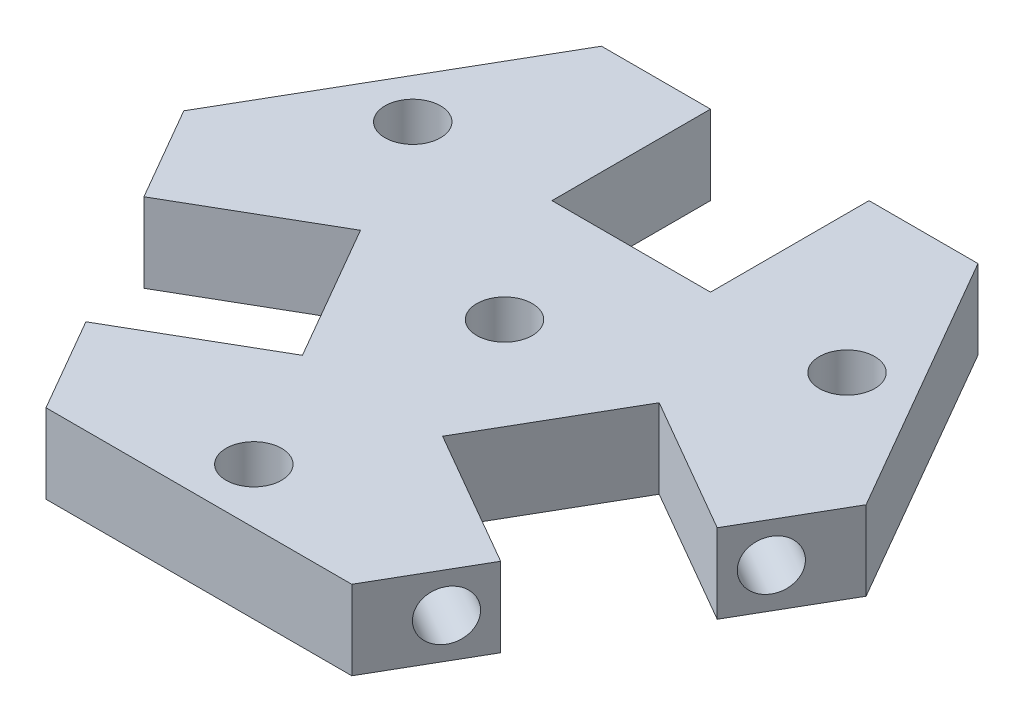
SolidWorks part; units mm, degrees
ref_plane "Front Plane" through (0, 0, 0) normal (0, 0, 1) x (1, 0, 0)
ref_plane "Top Plane" through (0, 0, 0) normal (0, 1, 0) x (1, 0, 0)
ref_plane "Right Plane" through (0, 0, 0) normal (1, 0, 0) x (0, 0, -1)
sketch "Sketch1" plane through (0, 0, 0) normal (0, 1, 0) x (1, 0, 0)
  line L1 (0, 16.5) -> (-14.2894, -8.25)
  line L2 (-14.2894, -8.25) -> (14.2894, -8.25)
  line L3 (14.2894, -8.25) -> (0, 16.5)
  line L4 (-10, 10.15) -> (10, 10.15)
  line L5 (-10, 10.15) -> (-10, 22.85)
  line L6 (-10, 22.85) -> (10, 22.85)
  line L7 (10, 10.15) -> (10, 22.85)
  line L8 (-10, 10.15) -> (10, 22.85) construction
  line L9 (-10, 22.85) -> (10, 10.15) construction
  line L17 (-14.7887, -20.0853) -> (-24.7887, -2.7647)
  line L18 (-13.7902, 3.5853) -> (-24.7887, -2.7647)
  line L19 (-11.9652, 0.4243) -> (-22.9637, -5.9257)
  line L20 (-3.7902, -13.7353) -> (-13.7902, 3.5853)
  line L21 (-6.35, 10.15) -> (6.35, 10.15)
  line L22 (-6.35, 10.15) -> (-6.35, 22.85)
  line L23 (-6.35, 22.85) -> (6.35, 22.85)
  line L24 (6.35, 10.15) -> (6.35, 22.85)
  line L25 (-6.35, 10.15) -> (6.35, 22.85) construction
  line L26 (-6.35, 22.85) -> (6.35, 10.15) construction
  line L27 (-5.6152, -10.5743) -> (-16.6137, -16.9243)
  line L28 (-3.7902, -13.7353) -> (-14.7887, -20.0853)
  line L29 (24.7887, -2.7647) -> (14.7887, -20.0853)
  line L30 (3.7902, -13.7353) -> (14.7887, -20.0853)
  line L31 (5.6152, -10.5743) -> (16.6137, -16.9243)
  line L32 (13.7902, 3.5853) -> (3.7902, -13.7353)
  line L33 (11.9652, 0.4243) -> (22.9637, -5.9257)
  line L34 (13.7902, 3.5853) -> (24.7887, -2.7647)
  line L35 (-10, 22.85) -> (14.7887, -20.0853)
  line L36 (10, 22.85) -> (-14.7887, -20.0853)
  line L37 (24.7887, -2.7647) -> (-24.7887, -2.7647)
  line L38 (-10, 22.85) -> (-24.7887, -2.7647)
  line L39 (10, 22.85) -> (24.7887, -2.7647)
  line L40 (14.7887, -20.0853) -> (-14.7887, -20.0853)
  line L41 (-24.7887, -2.7647) -> (-14.7887, -20.0853)
  line L42 (-14.7887, -20.0853) -> (-12.2487, -24.4847)
  line L43 (24.7887, -2.7647) -> (12.2487, -24.4847)
  line L44 (12.2487, -24.4847) -> (-12.2487, -24.4847)
  line L45 (-27.3287, 1.6347) -> (-15.08, 22.85)
  line L46 (-10, 22.85) -> (-15.08, 22.85)
  line L47 (-14.7887, -20.0853) -> (-27.3287, 1.6347)
  line L48 (15.08, 22.85) -> (27.3287, 1.6347)
  line L49 (24.7887, -2.7647) -> (27.3287, 1.6347)
  line L50 (-10, 22.85) -> (15.08, 22.85)
  circle A0 centre (0, 0) radius 8.25 construction
  circle A1 centre (0, 0) radius 2.2225
  circle A2 centre (0, -20.0853) radius 2.2225
  circle A3 centre (17.3943, 10.0426) radius 2.2225
  circle A4 centre (-17.3943, 10.0426) radius 2.2225
  dimension "D1" = 16.5
  dimension "D7" = 5.08
  dimension "D2" = 12.7
  dimension "D3" = 20
  dimension "D5" = 12.7
  dimension "D6" = 12.7
  dimension "D4" = 3
  dimension "D8" = 3
extrude "Boss-Extrude3" add sketch "Sketch1" along normal blind 6.35 contours L5 L38 L18 L20 L1 L4 | L37 L19 L20 L18 | L27 L36 L28 L20 | L36 L27 L17 | L40 L30 L32 L2 L20 L28 | L35 L31 L32 L30 | L31 L35 L29 | L29 L37 L33 | L37 L34 L32 L33 | L39 L7 L4 L3 L32 L34 | L7 L36 L24 L4 | L36 L6 L24 | L35 L5 L4 L22 | L6 L35 L22 | L37 L36 L35 L4 L1 L20 | L36 L21 L35 | L37 L32 L3 L4 L36 L35 | L32 L37 L35 | L35 L37 L36 L20 L2 L32 | L36 L37 L20 | L37 L35 L36 | L19 L37 L17 | L44 L43 L40 L42 | L50 L39 L49 L48 | L47 L38 L46 L45
sketch "Sketch2" plane through (19.7887, 0, 11.425) normal (0.866, 0, 0.5) x (0.5, 0, -0.866)
  line L0 (-6.35, 3.175) -> (-15.08, 3.175)
  line L1 (-6.35, 6.35) -> (-6.35, 0) construction
  line L2 (-15.08, 6.35) -> (-15.08, 0) construction
  line L3 (15.08, 3.175) -> (6.35, 3.175)
  line L4 (15.08, 6.35) -> (15.08, 0) construction
  line L5 (6.35, 6.35) -> (6.35, 0) construction
  circle A0 centre (-9.525, 3.175) radius 2.0003
  circle A1 centre (9.525, 3.175) radius 2.0003
  dimension "D1" = 3.175
  dimension "D3" = 19.05
extrude "Cut-Extrude1" cut sketch "Sketch2" against normal blind 6.35 contours L0 A0 | L0 A0 | L3 A1 | L3 A1
sketch "Sketch3" plane through (-19.7887, 0, 11.425) normal (-0.866, 0, 0.5) x (0.5, 0, 0.866)
  line L0 (-15.08, 3.175) -> (-6.35, 3.175)
  line L1 (-15.08, 6.35) -> (-15.08, 0) construction
  line L2 (-6.35, 6.35) -> (-6.35, 0) construction
  line L3 (6.35, 3.175) -> (15.08, 3.175)
  line L4 (6.35, 6.35) -> (6.35, 0) construction
  line L5 (15.08, 6.35) -> (15.08, 0) construction
  circle A0 centre (-9.525, 3.175) radius 2.0003
  circle A1 centre (9.525, 3.175) radius 2.0003
  dimension "D1" = 19.05
  dimension "D2" = 3.175
extrude "Cut-Extrude2" cut sketch "Sketch3" against normal blind 6.35 contours A0 | A1
sketch "Sketch4" plane through (0, 0, -22.85) normal (0, 0, -1) x (-1, 0, 0)
  line L0 (-15.08, 3.175) -> (-6.35, 3.175)
  line L1 (-15.08, 6.35) -> (-15.08, 0) construction
  line L2 (-6.35, 6.35) -> (-6.35, 0) construction
  line L3 (6.35, 3.175) -> (15.08, 3.175)
  line L4 (6.35, 6.35) -> (6.35, 0) construction
  line L5 (15.08, 6.35) -> (15.08, 0) construction
  circle A0 centre (-9.525, 3.175) radius 2.0003
  circle A1 centre (9.525, 3.175) radius 2.0003
  dimension "D1" = 19.05
  dimension "D2" = 3.175
extrude "Cut-Extrude3" cut sketch "Sketch4" against normal blind 6.35 contours A0 | A1
